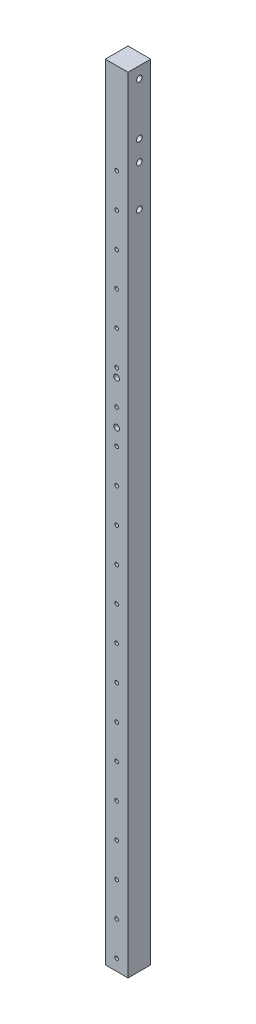
SolidWorks part; units mm, degrees
material "Alliage 1060"
ref_plane "Plan de face" through (0, 0, 0) normal (0, 0, 1) x (1, 0, 0)
ref_plane "Plan de dessus" through (0, 0, 0) normal (0, 1, 0) x (1, 0, 0)
ref_plane "Plan de droite" through (0, 0, 0) normal (1, 0, 0) x (0, 0, -1)
sketch "Esquisse1" plane through (0, 0, 0) normal (0, 1, 0) x (1, 0, 0)
  line L0 (-5, 5) -> (5, -5) construction
  line L1 (-5, 5) -> (5, 5)
  line L2 (-5, 5) -> (-5, -5)
  line L3 (-5, -5) -> (5, -5)
  line L4 (5, 5) -> (5, -5)
  dimension "D1" = 10
extrude "Boss.-Extru.1" add sketch "Esquisse1" along normal up to surface (345 mm away)
hole_wizard "Trou taraudé M3x0.51" positions "Esquisse2" profile "Esquisse3" tap size "M3x0.5" standard "Ansi Metric" end condition through all
sketch "Esquisse2" plane through (-5, 0, 0) normal (-1, 0, 0) x (0, 0, 1)
  line L0 (1.5535, 290.2) -> (-1.5535, 290.2) construction
  line L3 (-1.5535, 308.2) -> (1.5535, 308.2) construction
  point P41 (0, 340)
  point P44 (0, 317.2)
  point P47 (0, 308.2)
  point P49 (0, 290.2)
sketch "Esquisse3" plane through (-5, 340, 0) normal (0, 1, 0) x (0, 0, 1)
  line L0 (0, 0) -> (0, 10)
  line L1 (0, 10) -> (1.25, 10)
  line L2 (1.25, 10) -> (1.25, 0)
  line L5 (1.25, 0) -> (0, 0)
  line L11 (0, -6.35) -> (0, 107.95) construction
  dimension "Diamètre du trou pour taraudage jusqu'au prochain" = 2.5
  dimension "Profondeur du trou pour taraudage jusqu'au prochain" = 10
cosmetic thread "Filetage de perçage1"
cosmetic thread "Filetage de perçage2"
cosmetic thread "Filetage de perçage3"
cosmetic thread "Filetage de perçage4"
hole_wizard "Trou taraudé M2x0.41" positions "Esquisse4" profile "Esquisse5" tap size "M2x0.4" standard "Ansi Metric"
sketch "Esquisse4" plane through (0, 0, 5) normal (0, 0, 1) x (1, 0, 0)
  point P0 (0, 5)
  point P3 (0, 20)
  point P6 (0, 35)
  point P9 (0, 50)
  point P12 (0, 65)
  point P15 (0, 80)
  point P18 (0, 95)
  point P21 (0, 110)
  point P24 (0, 125)
  point P27 (0, 140)
  point P30 (0, 155)
  point P33 (0, 170)
  point P36 (0, 185)
  point P39 (0, 200)
  point P42 (0, 215)
  point P45 (0, 230)
  point P48 (0, 245)
  point P51 (0, 260)
  point P54 (0, 290)
  point P57 (0, 275)
  point P61 (0, 305)
sketch "Esquisse5" plane through (0, 5, 5) normal (1, 0, 0) x (0, -1, 0)
  line L0 (0, 0) -> (0, 6)
  line L1 (0, 6) -> (0.8, 6)
  line L2 (0.8, 6) -> (0.8, 0)
  line L5 (0.8, 0) -> (0, 0)
  line L10 (0, 6) -> (-0.8, 6) construction
  line L11 (0, -6.35) -> (0, 107.95) construction
  dimension "Diamètre du trou pour taraudage" = 1.6
  dimension "Profondeur du trou pour taraudage" = 6
  dimension "Angle de pointe" = 180
cosmetic thread "Filetage de perçage5"
cosmetic thread "Filetage de perçage6"
cosmetic thread "Filetage de perçage7"
cosmetic thread "Filetage de perçage8"
cosmetic thread "Filetage de perçage9"
cosmetic thread "Filetage de perçage10"
cosmetic thread "Filetage de perçage11"
cosmetic thread "Filetage de perçage12"
cosmetic thread "Filetage de perçage13"
cosmetic thread "Filetage de perçage14"
cosmetic thread "Filetage de perçage15"
cosmetic thread "Filetage de perçage16"
cosmetic thread "Filetage de perçage17"
cosmetic thread "Filetage de perçage18"
cosmetic thread "Filetage de perçage19"
cosmetic thread "Filetage de perçage20"
cosmetic thread "Filetage de perçage21"
cosmetic thread "Filetage de perçage22"
cosmetic thread "Filetage de perçage23"
cosmetic thread "Filetage de perçage24"
cosmetic thread "Filetage de perçage25"
hole_wizard "Trou taraudé M3x0.52" positions "Esquisse6" profile "Esquisse7" tap size "M3x0.5" standard "Ansi Metric" end condition through all
sketch "Esquisse6" plane through (0, 0, -5) normal (0, 0, -1) x (-1, 0, 0)
  point P0 (0, 226.2)
  point P3 (0, 207.2)
sketch "Esquisse7" plane through (0, 226.2, -5) normal (1, 0, 0) x (0, 1, 0)
  line L0 (0, 0) -> (0, 10)
  line L1 (0, 10) -> (1.25, 10)
  line L2 (1.25, 10) -> (1.25, 0)
  line L5 (1.25, 0) -> (0, 0)
  line L11 (0, -6.35) -> (0, 107.95) construction
  dimension "Diamètre du trou pour taraudage jusqu'au prochain" = 2.5
  dimension "Profondeur du trou pour taraudage jusqu'au prochain" = 10
cosmetic thread "Filetage de perçage26"
cosmetic thread "Filetage de perçage27"
